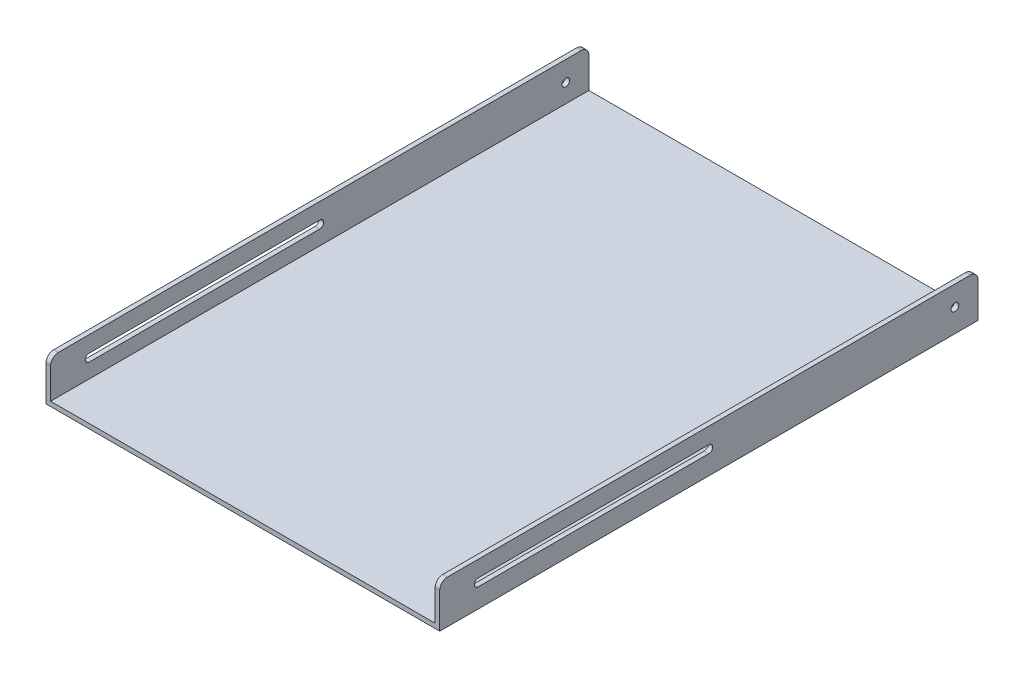
SolidWorks part; units mm, degrees
ref_plane "Front Plane" through (0, 0, 0) normal (0, 0, 1) x (1, 0, 0)
ref_plane "Top Plane" through (0, 0, 0) normal (0, 1, 0) x (1, 0, 0)
ref_plane "Right Plane" through (0, 0, 0) normal (1, 0, 0) x (0, 0, -1)
sketch "Sketch1" plane through (0, 0, 0) normal (0, 0, 1) x (1, 0, 0)
  line L0 (-250, 50) -> (-250, 0)
  line L1 (-250, 0) -> (250, 0)
  line L2 (250, 0) -> (250, 50)
  dimension "D1" = 500
  dimension "D2" = 50
  dimension "D3" = 50
  dimension "D4" = 250
extrude "Extrude-Thin1" add sketch "Sketch1" along normal mid plane 700 thin
sketch "Sketch2" plane through (256, 0, 0) normal (1, 0, 0) x (0, 0, -1)
  line L0 (350, -6) -> (350, 50) construction
  line L1 (-350, -6) -> (350, -6) construction
  line L2 (-300, 24) -> (0, 24) construction
  line L3 (-300, 29) -> (0, 29)
  line L4 (-300, 19) -> (0, 19)
  circle A0 centre (320, 24) radius 5
  arc A1 (-300, 29) -> (-300, 19) centre (-300, 24) ccw
  arc A2 (0, 19) -> (0, 29) centre (0, 24) ccw
  point P4 (350, 22)
  point P9 (-150, 24)
  dimension "D1" = 10
  dimension "D2" = 30
  dimension "D3" = 30
  dimension "D4" = 150
  dimension "D5" = 300
  dimension "D6" = 10
extrude "Cut-Extrude1" cut sketch "Sketch2" against normal through all
fillet "Fillet1" radius 10 4 edges at (253, 50, 350) (-253, 50, 350) (-253, 50, -350) (253, 50, -350)
